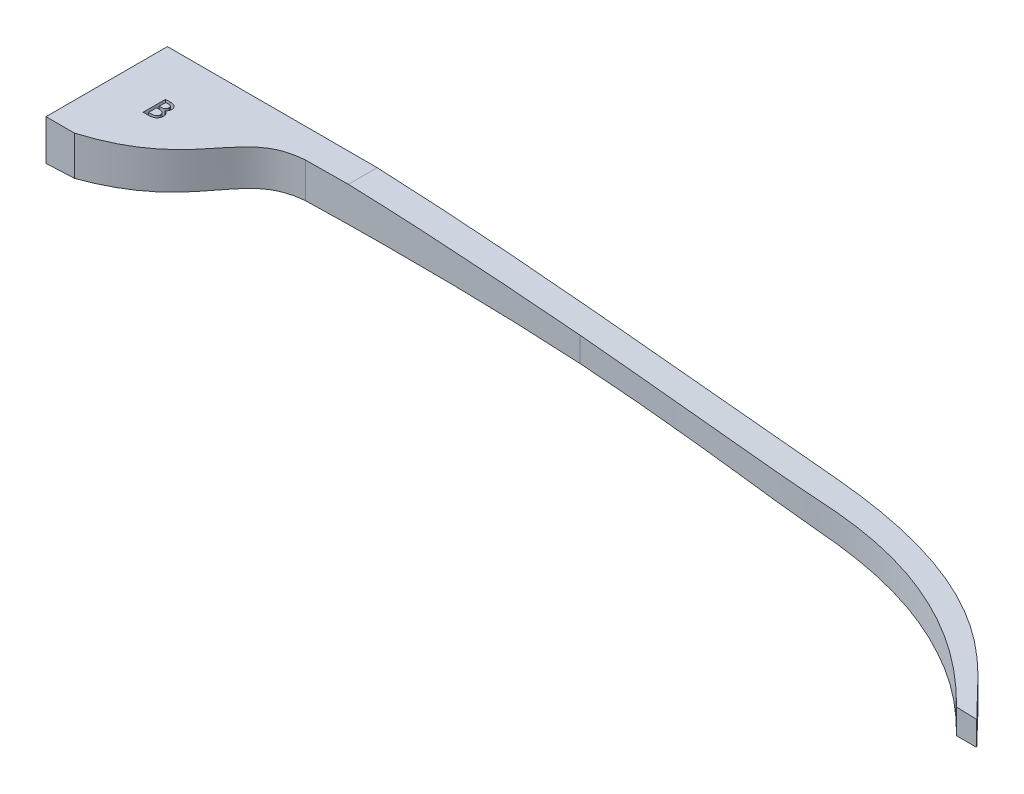
SolidWorks part; units mm, degrees
ref_plane "Front Plane" through (0, 0, 0) normal (0, 0, 1) x (1, 0, 0)
ref_plane "Top Plane" through (0, 0, 0) normal (0, 1, 0) x (1, 0, 0)
ref_plane "Right Plane" through (0, 0, 0) normal (1, 0, 0) x (0, 0, -1)
sketch "Sketch1" plane through (0, 0, 0) normal (0, 1, 0) x (1, 0, 0)
  line L1 (0, 0) -> (146.05, 0)
  line L2 (0, 0) -> (0, 19.05)
  line L3 (0, 19.05) -> (146.05, 19.05)
  line L4 (146.05, 0) -> (146.05, 19.05)
  dimension "D1" = 146.05
  dimension "D2" = 19.05
extrude "Boss-Extrude1" add sketch "Sketch1" along normal blind 12.7
sketch "Sketch3" plane through (0, 0, -19.05) normal (0, 0, -1) x (-1, 0, 0)
  line L0 (0, 12.7) -> (0, 0) construction
  line L1 (-146.05, 12.7) -> (-146.05, 0) construction
  spline S0 degree 3 poles (0, 6.35) (-26.7926, 7.5544) (-75.8961, 8.1392) (-124.0253, -1.1368) (-146.05, 0) knots 0 0 0 0 0.551608 1 1 1 1
  spline S1 degree 3 poles (0, 12.7) (-49.0772, 15.1643) (-97.2306, 5.0411) (-146.05, 3.81) knots 0 0 0 0 1 1 1 1
  point P6 (-80.6679, 5.4839)
  point P11 (0, 0)
  point P13 (-80.6679, 8.89)
  line M1 (-146.05, 0) -> (0, 0)
  line M2 (0, 0) -> (0, 12.7)
  line M3 (0, 12.7) -> (-146.05, 12.7)
  line M4 (-146.05, 12.7) -> (-146.05, 0)
  dimension "D1" = 6.35
  dimension "D2" = 3.81
  dimension "D3" = 4.445
  dimension "D4" = 3.6908
sketch "Sketch7" plane through (0, 12.7, 0) normal (0, 1, 0) x (1, 0, 0)
  text T0 "<b>B</b>"
  point P1 (2.6659, 2.6057)
  point P2 (6.5729, 8.2263)
extrude "Cut-Extrude6" cut sketch "Sketch7" against normal blind 1.905
sketch "Sketch4" plane through (0, 12.7, 0) normal (0, 1, 0) x (1, 0, 0)
  line L0 (146.05, 19.05) -> (0, 19.05) construction
  line L3 (4.4767, 0) -> (142.875, 0)
  line L4 (146.05, 0) -> (146.05, 19.05)
  line L5 (146.05, 19.05) -> (104.3032, 19.05)
  line L6 (0, 0) -> (146.05, 0) construction
  line L7 (146.05, 0) -> (146.05, 19.05) construction
  spline S0 degree 3 poles (4.4767, 0) (17.7258, 4.0431) (17.0053, 14.2049) (37.6932, 14.9861) (95.0665, 14.824) (108.0685, 14.714) (127.2268, 16.0497) (142.875, 0) knots 0 0 0 0 0.256127 0.322877 0.629203 0.700745 1 1 1 1
  spline S1 degree 3 poles (104.3032, 19.05) (131.3235, 19.1838) (139.2243, 6.6595) (146.05, 0) knots 0 0 0 0 1 1 1 1
  spline S2 degree 1 poles (26.2195, 14.4658) (68.9239, 14.8611) knots 0 0 1 1
  point P6 (0, 0)
  point P13 (0, 0)
  point P17 (0, 0)
  point P18 (0, 0)
  point P19 (26.0226, 11.7378)
  point P20 (94.5373, 16.2492)
  point P21 (0, 0)
  point P22 (99.2036, 15.3249)
  point P23 (0, 0)
  point P24 (100.1486, 14.2483)
  point P26 (0, 0)
  point P27 (26.4138, 13.3599)
  point P28 (0, 0)
  point P29 (101.7607, 15.5107)
  point P30 (0, 0)
  point P31 (68.9239, 14.7754)
  line M2 (146.05, 19.05) -> (0, 19.05)
  line M4 (0, 0) -> (146.05, 0)
  dimension "D1" = 3.175
extrude "Cut-Extrude2" cut sketch "Sketch4" against normal blind 19.05 contours S2 S0 M4 | S1 L4 M2
extrude "Cut-Extrude3" cut sketch "Sketch3" against normal through all contours S0 M2 M1 | S1 M3 M4
sketch "Sketch5" plane through (0, 0, 0) normal (-1, 0, 0) x (0, 0, 1)
  line L0 (0, 6.35) -> (-19.05, 6.35) construction
  line L1 (-5.715, 6.35) -> (-12.7, 6.35)
  line L2 (-5.715, 6.35) -> (-5.715, 10.16)
  line L3 (-5.715, 10.16) -> (-12.7, 10.16)
  line L4 (-12.7, 6.35) -> (-12.7, 10.16)
  line L5 (-19.05, 12.7) -> (-19.05, 6.35) construction
  dimension "D1" = 3.81
  dimension "D2" = 6.985
  dimension "D3" = 6.35
extrude "Cut-Extrude4" cut sketch "Sketch5" against normal blind 6.35
